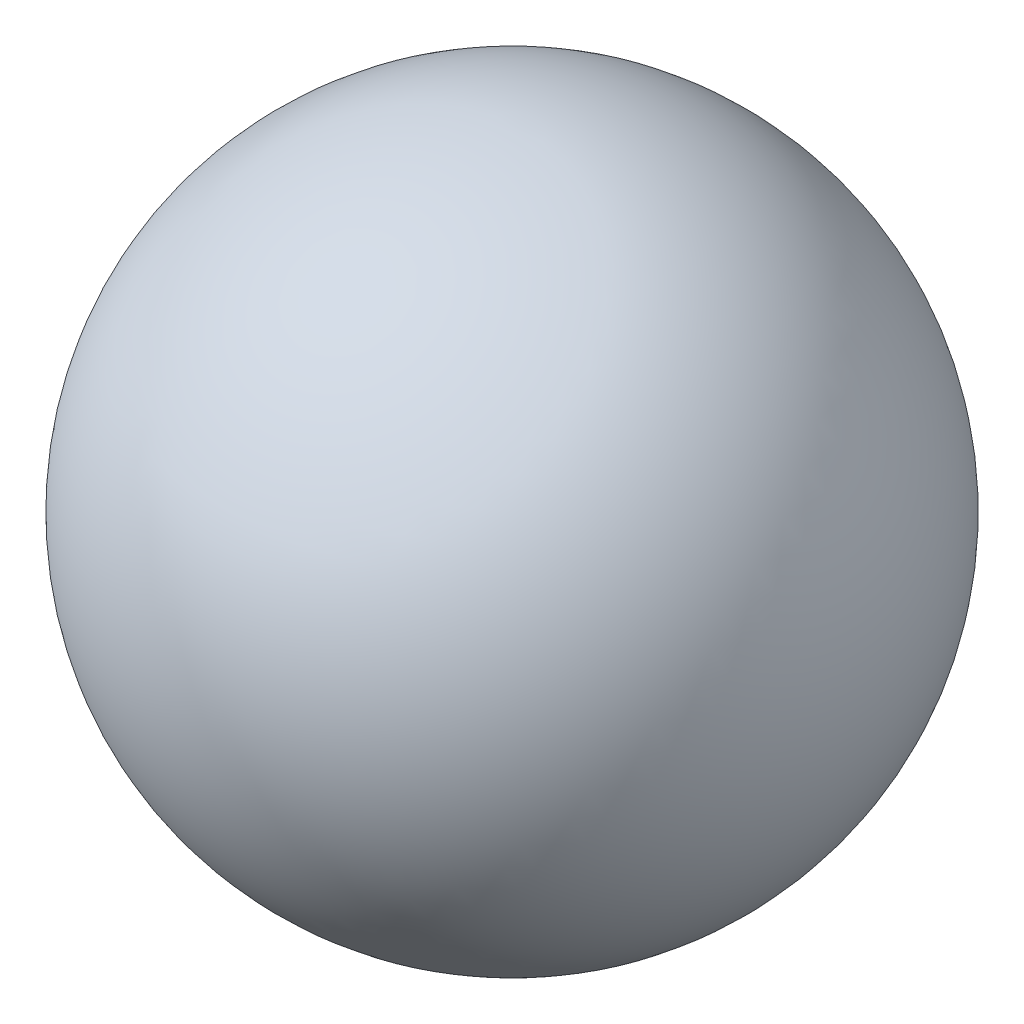
SolidWorks part; units mm, degrees
ref_plane "Front Plane" through (0, 0, 0) normal (0, 0, 1) x (1, 0, 0)
ref_plane "Top Plane" through (0, 0, 0) normal (0, 1, 0) x (1, 0, 0)
ref_plane "Right Plane" through (0, 0, 0) normal (1, 0, 0) x (0, 0, -1)
sketch "Sketch1" plane through (0, 0, 0) normal (0, 0, 1) x (1, 0, 0)
  line L0 (0, 28.575) -> (0, -28.575)
  arc A0 (0, -28.575) -> (0, 28.575) centre (0, 0) ccw
  dimension "D1" = 57.15
revolve "Revolve1" add sketch "Sketch1" angle 360 about L0
